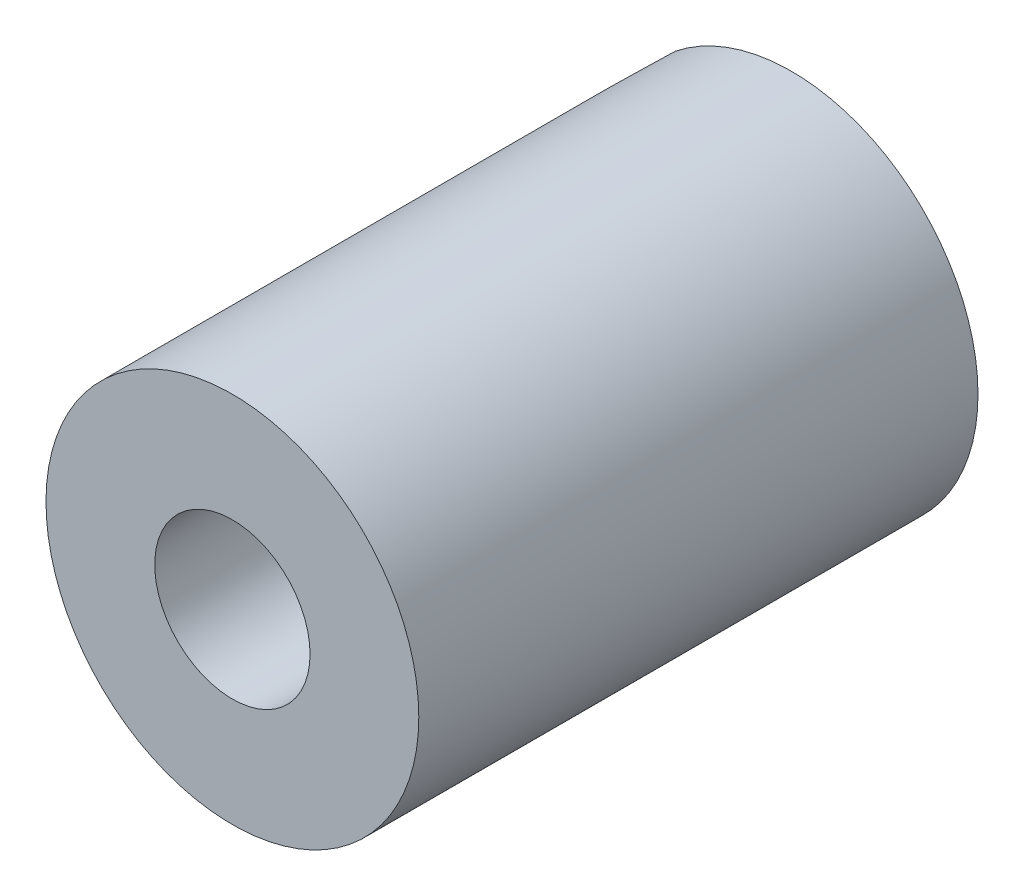
SolidWorks part; units mm, degrees
ref_plane "Face" through (0, 0, 0) normal (0, 0, 1) x (1, 0, 0)
ref_plane "Dessus" through (0, 0, 0) normal (0, 1, 0) x (1, 0, 0)
ref_plane "Droite" through (0, 0, 0) normal (1, 0, 0) x (0, 0, -1)
sketch "Esquisse1" plane through (0, 0, 0) normal (0, 0, 1) x (1, 0, 0)
  circle A0 centre (0, 0) radius 3
  circle A1 centre (0, 0) radius 1.25
  dimension "D1" = 6
  dimension "D2" = 2.5
extrude "Base-Extrusion" add sketch "Esquisse1" along normal blind 9
sketch "Esquisse2" plane through (0, 0, 0) normal (0, 1, 0) x (1, 0, 0)
  circle A0 centre (-8.8, 1) radius 7
  dimension "D1" = 14
  dimension "D2" = 8.8
  dimension "D3" = 1
extrude "Enlèv. mat.-Extru.1" cut sketch "Esquisse2" against normal mid plane 10
